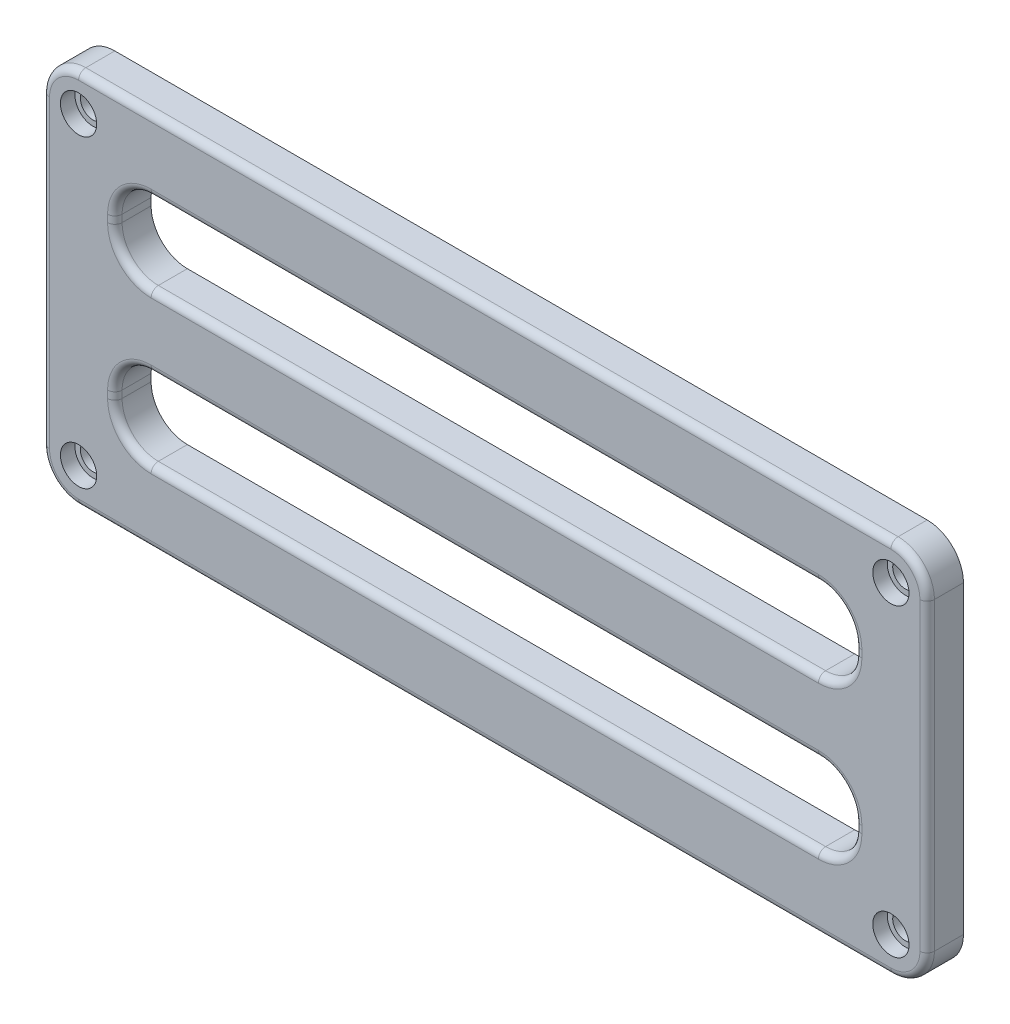
SolidWorks part; units mm, degrees
ref_plane "Front Plane" through (0, 0, 0) normal (0, 0, 1) x (1, 0, 0)
ref_plane "Top Plane" through (0, 0, 0) normal (0, 1, 0) x (1, 0, 0)
ref_plane "Right Plane" through (0, 0, 0) normal (1, 0, 0) x (0, 0, -1)
sketch "Sketch1" plane through (0, 0, 0) normal (0, 0, 1) x (1, 0, 0)
  line L0 (0, 0) -> (102, 0)
  line L1 (102, 0) -> (102, 32)
  line L2 (102, 32) -> (0, 32)
  line L3 (0, 32) -> (0, 0)
  line L4 (-10, -10) -> (112, -10)
  line L5 (112, -10) -> (112, 42)
  line L6 (112, 42) -> (-10, 42)
  line L7 (-10, 42) -> (-10, -10)
  dimension "D1" = 102
  dimension "D2" = 32
  dimension "D3" = 10
  dimension "D4" = 10
  dimension "D5" = 10
  dimension "D6" = 10
extrude "Boss-Extrude1" add sketch "Sketch1" along normal blind 5
sketch "Sketch2" plane through (0, 0, 5) normal (0, 0, 1) x (1, 0, 0)
  line L1 (0, 21) -> (102, 21)
  line L4 (0, 16) -> (0, 21)
  line L5 (0, 32) -> (0, 0) construction
  line L6 (0, 16) -> (0, 11)
  line L10 (102, 16) -> (102, 21)
  line L11 (102, 0) -> (102, 32) construction
  line L12 (102, 16) -> (102, 11)
  line L21 (0, 11) -> (102, 11)
  dimension "D3" = 5
  dimension "D4" = 5
  dimension "D5" = 5
  dimension "D6" = 5
extrude "Boss-Extrude2" add sketch "Sketch2" against normal blind 5
sketch "Sketch5" plane through (0, 0, 5) normal (0, 0, 1) x (1, 0, 0)
  line L4 (-10, 42) -> (-10, -10) construction
  line L5 (112, -10) -> (112, 42) construction
  line L6 (-10, -10) -> (112, -10) construction
  line L7 (112, 42) -> (-10, 42) construction
  line L8 (112, 42) -> (-10, 42) construction
  line L9 (112, -10) -> (112, 42) construction
  line L10 (-10, -10) -> (112, -10) construction
  line L11 (-10, 42) -> (-10, -10) construction
  circle A0 centre (-5, 37) radius 1.75
  circle A1 centre (107, 37) radius 1.75
  circle A2 centre (107, -5) radius 1.75
  circle A3 centre (-5, -5) radius 1.75
  dimension "D1" = 3.5
  dimension "D2" = 3.5
  dimension "D3" = 3.5
  dimension "D4" = 3.5
  dimension "D5" = 5
  dimension "D6" = 5
  dimension "D7" = 5
  dimension "D8" = 5
  dimension "D9" = 5
  dimension "D10" = 5
  dimension "D11" = 5
  dimension "D12" = 5
extrude "Cut-Extrude2" cut sketch "Sketch5" against normal through all
sketch "Sketch6" plane through (0, 0, 5) normal (0, 0, 1) x (1, 0, 0)
  circle A0 centre (-5, 37) radius 2.5
  circle A1 centre (107, 37) radius 2.5
  circle A2 centre (107, -5) radius 2.5
  circle A3 centre (-5, -5) radius 2.5
  dimension "D1" = 5
  dimension "D2" = 5
  dimension "D3" = 5
  dimension "D4" = 5
extrude "Cut-Extrude3" cut sketch "Sketch6" against normal blind 2
fillet "Fillet1" radius 5 12 edges at (0, 11, 2.5) (102, 0, 2.5) (102, 11, 2.5) (0, 0, 2.5) (0, 21, 2.5) (102, 21, 2.5) (102, 32, 2.5) (0, 32, 2.5) (-10, 42, 2.5) (112, 42, 2.5) (112, -10, 2.5) (-10, -10, 2.5)
fillet "Fillet2" radius 1 24 edges at (1.4645, 9.5355, 5) (0, 5.5, 5) (1.4645, 1.4645, 5) (51, 0, 5) (100.5355, 1.4645, 5) (102, 5.5, 5) (100.5355, 9.5355, 5) (100.5355, 30.5355, 5) (102, 26.5, 5) (100.5355, 22.4645, 5) (51, 21, 5) (1.4645, 22.4645, 5) (0, 26.5, 5) (1.4645, 30.5355, 5) (-8.5355, -8.5355, 5) (-10, 16, 5) (-8.5355, 40.5355, 5) (51, 42, 5) (110.5355, 40.5355, 5) (112, 16, 5) (110.5355, -8.5355, 5) (51, 11, 5) (51, 32, 5) (51, -10, 5)
